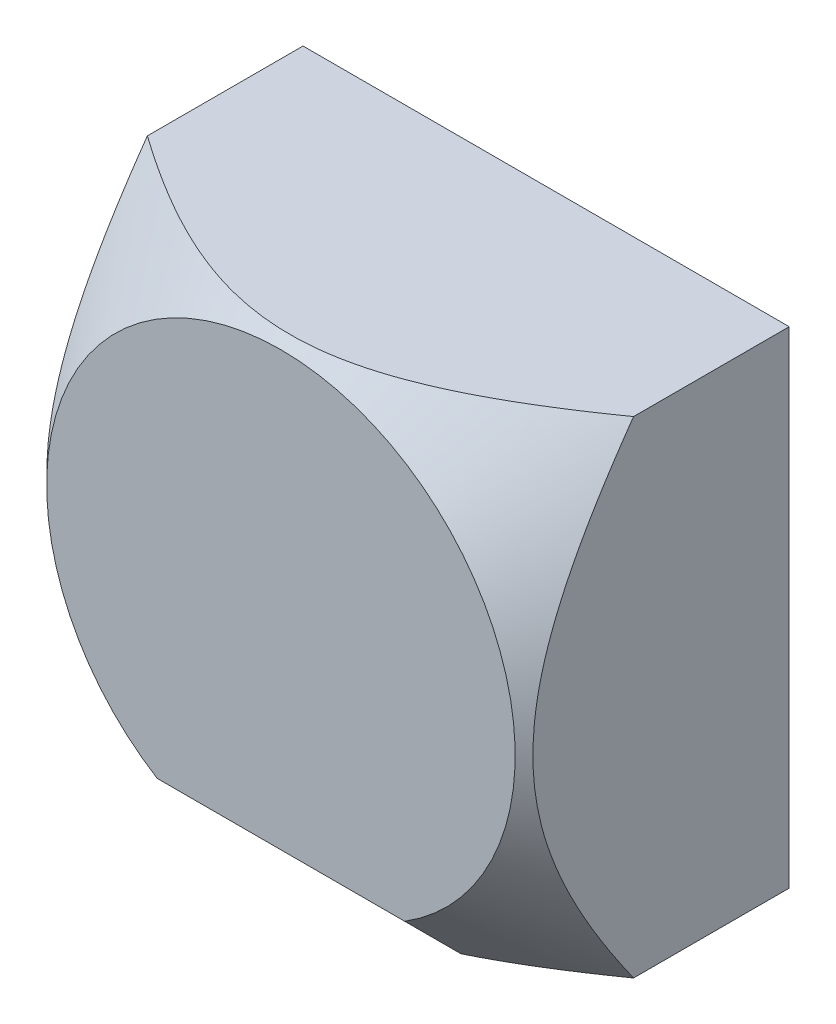
SolidWorks part; units mm, degrees
ref_plane "Alzado" through (0, 0, 0) normal (0, 0, 1) x (1, 0, 0)
ref_plane "Planta" through (0, 0, 0) normal (0, 1, 0) x (1, 0, 0)
ref_plane "Vista lateral" through (0, 0, 0) normal (1, 0, 0) x (0, 0, -1)
sketch "Croquis1" plane through (0, 0, 0) normal (0, 0, 1) x (1, 0, 0)
  line L1 (-27.5, 27.5) -> (27.5, 27.5)
  line L2 (-27.5, 27.5) -> (-27.5, -27.5)
  line L3 (-27.5, -27.5) -> (27.5, -27.5)
  line L4 (27.5, 27.5) -> (27.5, -27.5)
  line L5 (-27.5, 27.5) -> (27.5, -27.5) construction
  line L6 (-27.5, -27.5) -> (27.5, 27.5) construction
  point P0 (0, 0)
  dimension "D1" = 55
  dimension "D2" = 55
extrude "Saliente-Extruir1" add sketch "Croquis1" against normal blind 30
sketch "Croquis2" plane through (0, 0, 0) normal (1, 0, 0) x (0, 0, -1)
  line L0 (0, 26.5) -> (0, 46.5)
  line L2 (0, 46.5) -> (20, 46.5)
  line L3 (20, 46.5) -> (0, 26.5)
  line L4 (0, 0) -> (-13.6317, 0) construction
  dimension "D1" = 20
  dimension "D2" = 20
  dimension "D3" = 26.5
revolve "Cortar-Revolución1" cut sketch "Croquis2" angle 360 about L4
sketch "Croquis3" plane through (27.5, 0, 0) normal (1, 0, 0) x (0, 0, -1)
  line L0 (5, 27.5) -> (0, 27.5)
  line L1 (12.3909, 27.5) -> (1, 27.5) construction
  line L2 (0, 22.5) -> (0, 27.5)
  line L4 (0, 26.5) -> (0, -26.5) construction
  line L5 (5, 27.5) -> (0, 22.5)
  line L6 (0, 22.5) -> (0.0898, 22.5)
  line L7 (0, -22.5) -> (0, -27.5)
  line L8 (5, -27.5) -> (0, -27.5)
  line L9 (1, -27.5) -> (12.3909, -27.5) construction
  line L10 (5, -27.5) -> (0, -22.5)
  dimension "D1" = 5
  dimension "D2" = 5
  dimension "D3" = 5
  dimension "D4" = 5
extrude "Cortar-Extruir1" cut sketch "Croquis3" against normal up to next contours L7 L8 L10
